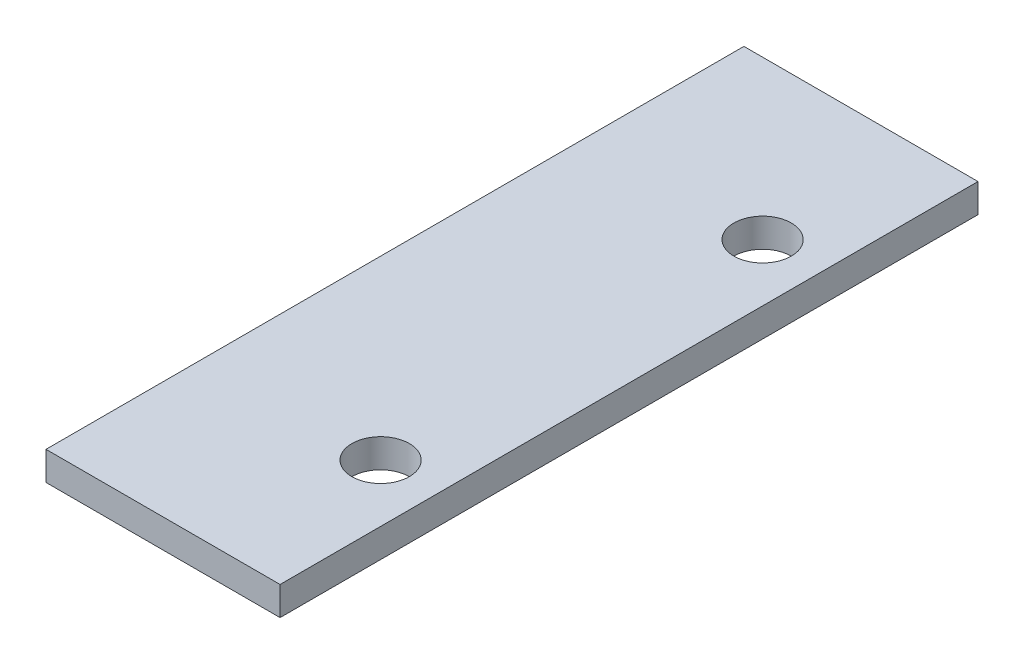
SolidWorks part; units mm, degrees
ref_plane "Front Plane" through (0, 0, 0) normal (0, 0, 1) x (1, 0, 0)
ref_plane "Top Plane" through (0, 0, 0) normal (0, 1, 0) x (1, 0, 0)
ref_plane "Right Plane" through (0, 0, 0) normal (1, 0, 0) x (0, 0, -1)
sketch "Sketch1" plane through (0, 0, 0) normal (0, 1, 0) x (1, 0, 0)
  line L1 (-50.7326, 4.9563) -> (-34.4326, 4.9563)
  line L2 (-50.7326, 4.9563) -> (-50.7326, -43.6437)
  line L3 (-50.7326, -43.6437) -> (-34.4326, -43.6437)
  line L4 (-34.4326, 4.9563) -> (-34.4326, -43.6437)
  circle A0 centre (-38.4326, -6.0437) radius 2
  circle A1 centre (-38.4326, -32.6437) radius 2
  dimension "D3" = 4
  dimension "D4" = 4
  dimension "D5" = 11
  dimension "D6" = 4
  dimension "D7" = 11
  dimension "D1" = 16.3
  dimension "D2" = 48.6
extrude "Boss-Extrude1" add sketch "Sketch1" along normal blind 2
equation "\"D6@Sketch1\"=\"D4@Sketch1\""
equation "\"D5@Sketch1\"=9.00mm+\"D3@Sketch1\"/2"
equation "\"D7@Sketch1\"=9.00mm+\"D6@Sketch1\"/2"
